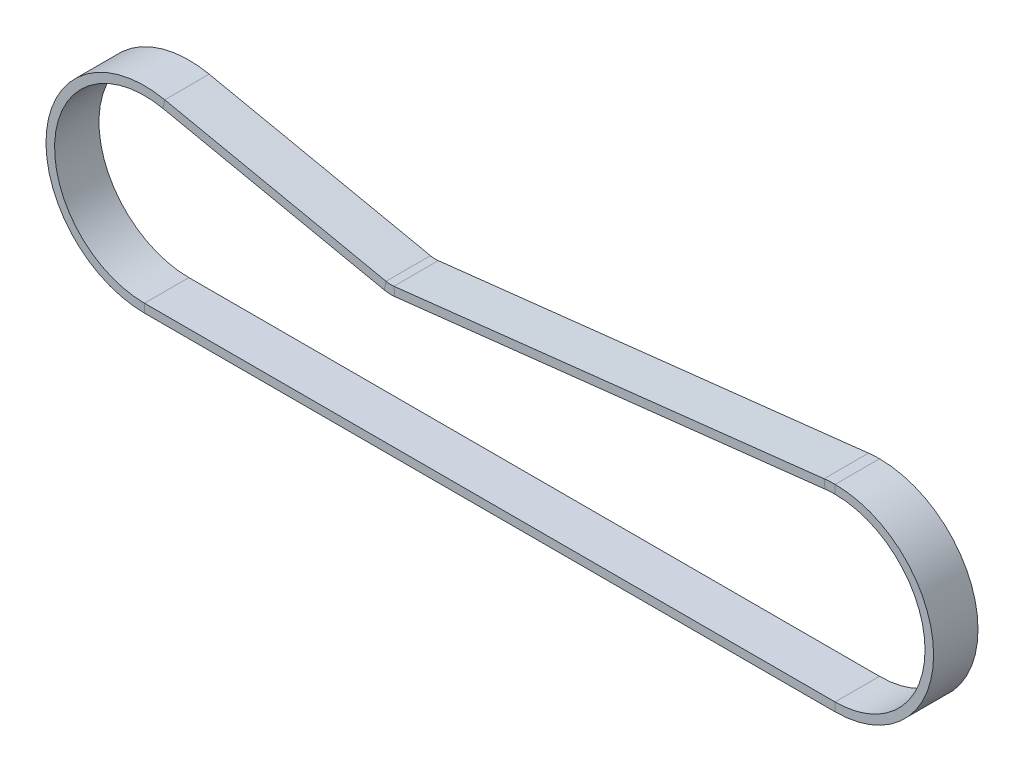
SolidWorks part; units mm, degrees
ref_plane "Front Plane" through (0, 0, 0) normal (0, 0, 1) x (1, 0, 0)
ref_plane "Top Plane" through (0, 0, 0) normal (0, 1, 0) x (1, 0, 0)
ref_plane "Right Plane" through (0, 0, 0) normal (1, 0, 0) x (0, 0, -1)
sketch "Sketch1" plane through (0, 0, 0) normal (0, 0, 1) x (1, 0, 0)
  line L0 (-2.1354, 18.9788) -> (-89.3437, 9.1668)
  line L1 (-91.208, 9.2556) -> (-136.0696, 18.6898)
  line L2 (-140, -19.0986) -> (0, -19.0986)
  arc A0 (0, -19.0986) -> (-2.1354, 18.9788) centre (0, 0) ccw
  arc A1 (-136.0696, 18.6898) -> (-140, -19.0986) centre (-140, 0) ccw
  arc A2 (-91.208, 9.2556) -> (-89.3437, 9.1668) centre (-90, 15) ccw
  circle A7 centre (-90, 15) radius 5 construction
  circle A8 centre (-90, 15) radius 5 construction
  circle A9 centre (0, 0) radius 19.0986 construction
  circle A10 centre (0, 0) radius 19.0986 construction
  circle A11 centre (-140, 0) radius 19.0986 construction
  circle A12 centre (-140, 0) radius 19.0986 construction
  dimension "D1" = 0.87
  dimension "D2" = 0
  dimension "D3" = 0
sketch "Sketch2" plane through (0, 0, 0) normal (1, 0, 0) x (0, 0, -1)
  line L0 (0, 19.0986) -> (0, -19.0986) construction
  line L1 (4.5, 18.2286) -> (-4.5, 18.2286)
  line L2 (4.5, 18.2286) -> (4.5, 19.9686)
  line L3 (4.5, 19.9686) -> (-4.5, 19.9686)
  line L4 (-4.5, 18.2286) -> (-4.5, 19.9686)
  line L5 (4.5, 18.2286) -> (-4.5, 19.9686) construction
  line L6 (4.5, 19.9686) -> (-4.5, 18.2286) construction
  line L7 (0, 19.0986) -> (0, -19.0986) construction
  point P0 (0, 19.0986)
  dimension "D1" = 1.74
  dimension "D2" = 9
sweep "Sweep1" add profiles "Sketch2" path "Sketch1"
equation "\"D1@Sketch2\"=3.8-2.06"
equation "\"D1@Sketch1\"=(3.8-2.06)/2"
